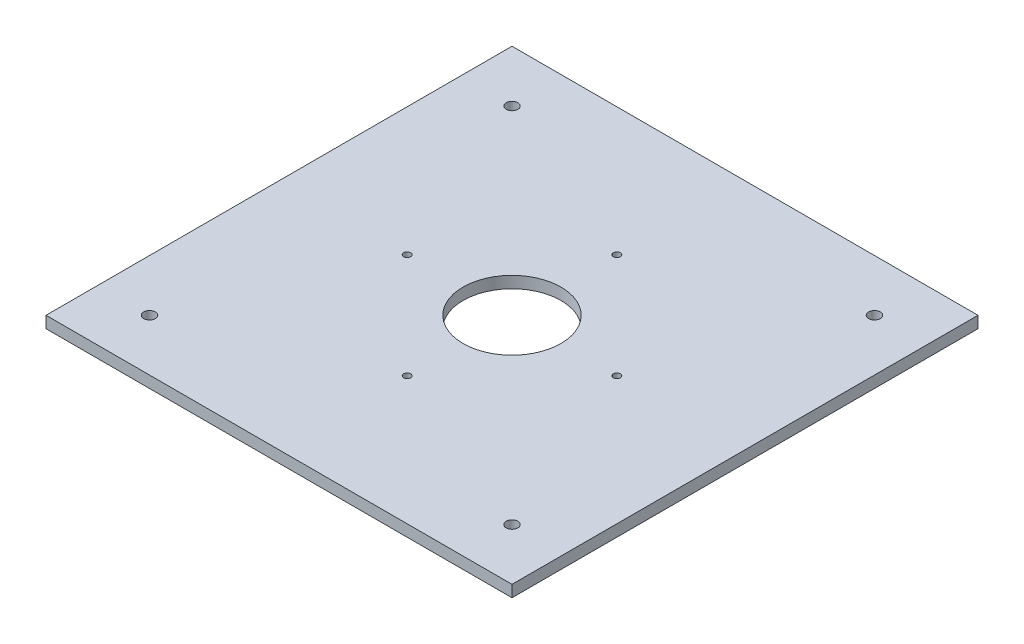
SolidWorks part; units mm, degrees
material "Acrylic (Medium-high impact)"
ref_plane "Front Plane" through (0, 0, 0) normal (0, 0, 1) x (1, 0, 0)
ref_plane "Top Plane" through (0, 0, 0) normal (0, 1, 0) x (1, 0, 0)
ref_plane "Right Plane" through (0, 0, 0) normal (1, 0, 0) x (0, 0, -1)
sketch "Sketch1" plane through (0, 0, 0) normal (0, 1, 0) x (1, 0, 0)
  line L1 (-100, 100) -> (100, 100)
  line L2 (-100, 100) -> (-100, -100)
  line L3 (-100, -100) -> (100, -100)
  line L4 (100, 100) -> (100, -100)
  line L5 (-100, 100) -> (100, -100) construction
  line L6 (-100, -100) -> (100, 100) construction
  point P0 (0, 0)
  dimension "D1" = 200
  dimension "D2" = 200
extrude "Boss-Extrude1" add sketch "Sketch1" along normal blind 5
sketch "Sketch2" plane through (0, 5, 0) normal (0, 1, 0) x (1, 0, 0)
  line L0 (0, 0) -> (100, 100) construction
  circle A2 centre (77.7817, 77.7817) radius 2.5
  circle A3 centre (77.7817, -77.7817) radius 2.5
  circle A4 centre (-77.7817, -77.7817) radius 2.5
  circle A5 centre (-77.7817, 77.7817) radius 2.5
  point P17 (0, 0)
  dimension "D1" = 5
  dimension "D2" = 110
  dimension "D3" = 4
extrude "Cut-Extrude1" cut sketch "Sketch2" against normal blind 5
sketch "Sketch3" plane through (0, 5, 0) normal (0, 1, 0) x (1, 0, 0)
  circle A0 centre (0, 0) radius 60 construction
  circle A1 centre (0, -45) radius 1.5
  circle A2 centre (-45, 0) radius 1.5
  circle A3 centre (0, 45) radius 1.5
  circle A4 centre (45, 0) radius 1.5
  point P14 (0, 0)
  dimension "D1" = 120
  dimension "D3" = 3
  dimension "D4" = 45
  dimension "D2" = 4
extrude "Cut-Extrude2" cut sketch "Sketch3" against normal blind 5
sketch "Sketch4" plane through (0, 5, 0) normal (0, 1, 0) x (1, 0, 0)
  circle A1 centre (0, 0) radius 21
  dimension "D1" = 42
extrude "Cut-Extrude3" cut sketch "Sketch4" against normal blind 7
sketch "Sketch5" plane through (0, 5, 0) normal (0, 1, 0) x (1, 0, 0)
  point P0 (-0.6523, -48.9465)
